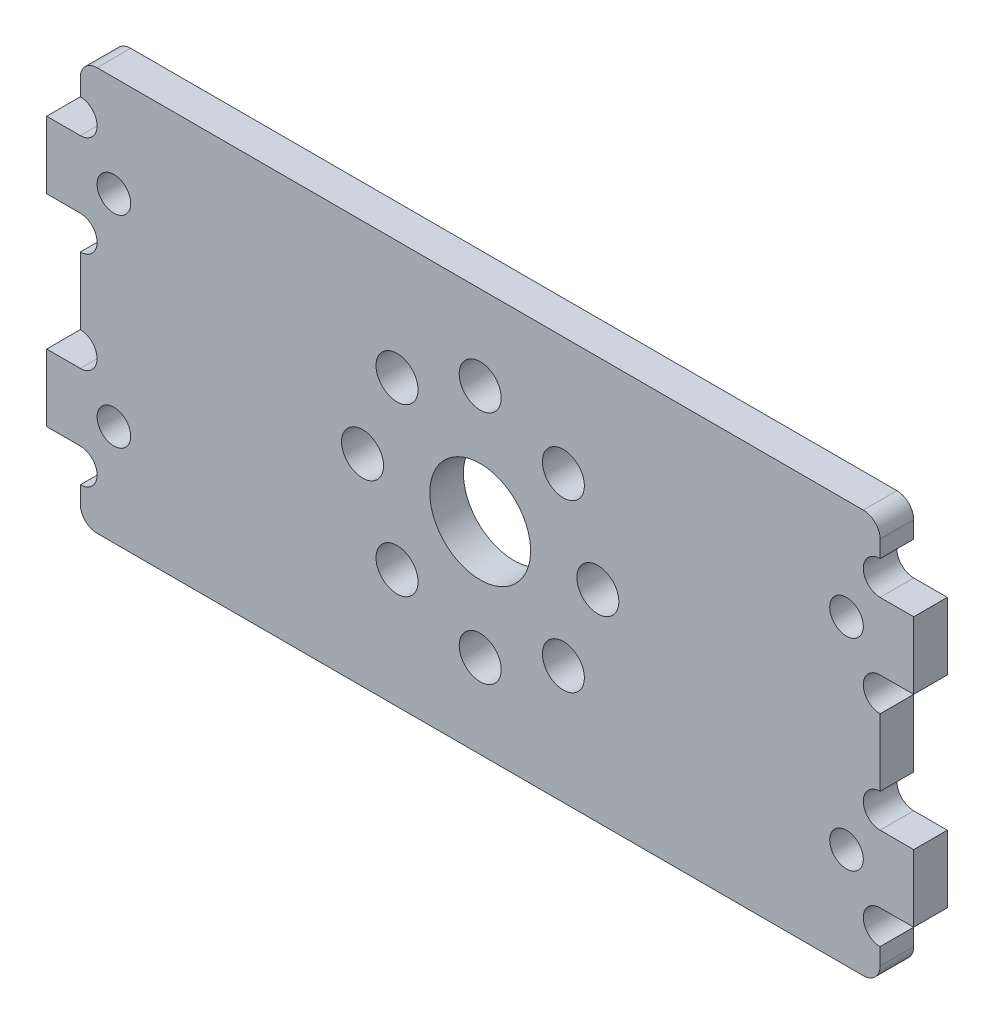
SolidWorks part; units mm, degrees
material "自訂玻璃纖維"
ref_plane "前基準面" through (0, 0, 0) normal (0, 0, 1) x (1, 0, 0)
ref_plane "上基準面" through (0, 0, 0) normal (0, 1, 0) x (1, 0, 0)
ref_plane "右基準面" through (0, 0, 0) normal (1, 0, 0) x (0, 0, -1)
sketch "草圖1" plane through (0, 0, 0) normal (0, 0, 1) x (1, 0, 0)
  line L0 (21.2594, 6.2775) -> (21.2594, 4.2775)
  line L1 (-26.3406, 6.2775) -> (21.2594, 6.2775)
  line L2 (-26.3406, 6.2775) -> (-26.3406, 4.2775)
  line L3 (-26.3406, -17.7225) -> (21.2594, -17.7225)
  line L4 (21.2594, 2.2775) -> (23.2594, 2.2775)
  line L5 (23.2594, 2.2775) -> (23.2594, -1.7225)
  line L6 (23.2594, -1.7225) -> (21.2594, -1.7225)
  line L7 (21.2594, -15.7225) -> (21.2594, -17.7225)
  line L8 (21.2594, -3.7225) -> (21.2594, -7.7225)
  line L9 (23.2594, -9.7225) -> (21.2594, -9.7225)
  line L10 (23.2594, -13.7225) -> (23.2594, -9.7225)
  line L11 (21.2594, -13.7225) -> (23.2594, -13.7225)
  line L12 (-26.3406, -3.7225) -> (-26.3406, -7.7225)
  line L13 (-26.3406, -13.7225) -> (-28.3406, -13.7225)
  line L14 (-28.3406, -13.7225) -> (-28.3406, -9.7225)
  line L15 (-28.3406, -9.7225) -> (-26.3406, -9.7225)
  line L16 (-28.3406, -1.7225) -> (-26.3406, -1.7225)
  line L17 (-28.3406, 2.2775) -> (-28.3406, -1.7225)
  line L18 (-26.3406, 2.2775) -> (-28.3406, 2.2775)
  line L19 (-26.3406, -15.7225) -> (-26.3406, -17.7225)
  circle A0 centre (-20.5406, -5.7225) radius 1
  circle A1 centre (15.4594, -5.7225) radius 1
  arc A2 (21.2594, 2.2775) -> (21.2594, 4.2775) centre (21.2594, 3.2775) cw
  arc A3 (21.2594, -1.7225) -> (21.2594, -3.7225) centre (21.2594, -2.7225) ccw
  arc A4 (21.2594, -9.7225) -> (21.2594, -7.7225) centre (21.2594, -8.7225) cw
  arc A5 (21.2594, -13.7225) -> (21.2594, -15.7225) centre (21.2594, -14.7225) ccw
  arc A6 (-26.3406, -13.7225) -> (-26.3406, -15.7225) centre (-26.3406, -14.7225) cw
  arc A7 (-26.3406, -9.7225) -> (-26.3406, -7.7225) centre (-26.3406, -8.7225) ccw
  arc A8 (-26.3406, -1.7225) -> (-26.3406, -3.7225) centre (-26.3406, -2.7225) cw
  arc A9 (-26.3406, 2.2775) -> (-26.3406, 4.2775) centre (-26.3406, 3.2775) ccw
  dimension "D6" = 4
  dimension "D3" = 2
  dimension "D4" = 4
  dimension "D1" = 47.6
  dimension "D2" = 24
extrude "填料-伸長2" add sketch "草圖1" along normal blind 2
sketch "草圖3" plane through (0, 0, 2) normal (0, 0, 1) x (1, 0, 0)
  circle A0 centre (19.2594, -5.7225) radius 1
  circle A1 centre (15.4594, -5.7225) radius 1 construction
  circle A2 centre (-24.3406, -3.7225) radius 1
  dimension "D1" = 2
  dimension "D2" = 0
extrude "除料-伸長1" cut sketch "草圖3" against normal blind 2
sketch "草圖4" plane through (0, 0, 0) normal (0, 0, -1) x (-1, 0, 0)
  circle A0 centre (-15.4594, -5.7225) radius 1
  circle A1 centre (20.5406, -5.7225) radius 1
extrude "填料-伸長4" add sketch "草圖4" against normal blind 2
sketch "草圖5" plane through (0, 0, 0) normal (0, 0, -1) x (-1, 0, 0)
  line L0 (26.3406, -17.7225) -> (-21.2594, -17.7225) construction
  circle A0 centre (2.5406, -5.7225) radius 3
  circle A1 centre (2.5406, 1.2775) radius 1.25
  circle A2 centre (7.4904, -0.7727) radius 1.25
  circle A3 centre (9.5406, -5.7225) radius 1.25
  circle A4 centre (7.4904, -10.6722) radius 1.25
  circle A5 centre (2.5406, -12.7225) radius 1.25
  circle A6 centre (-2.4091, -10.6722) radius 1.25
  circle A7 centre (-4.4594, -5.7225) radius 1.25
  circle A8 centre (-2.4091, -0.7727) radius 1.25
  point P20 (2.5406, -3.7225)
  point P24 (2.5406, -5.7225)
  dimension "D1" = 2.5
  dimension "D2" = 6
  dimension "D3" = 7
  dimension "D5" = 12
  dimension "D4" = 8
extrude "除料-伸長2" cut sketch "草圖5" against normal blind 2
sketch "草圖6" plane through (0, 0, 0) normal (0, 0, -1) x (-1, 0, 0)
  circle A0 centre (-19.2594, -5.7225) radius 1
  circle A1 centre (24.3406, -3.7225) radius 1
extrude "填料-伸長6" add sketch "草圖6" against normal blind 2
sketch "草圖7" plane through (0, 0, 0) normal (0, 0, -1) x (-1, 0, 0)
  line L0 (-21.2594, 6.2775) -> (26.3406, 6.2775) construction
  line L1 (26.3406, -17.7225) -> (-21.2594, -17.7225) construction
  line L3 (26.3406, 6.2775) -> (26.3406, 4.2775) construction
  circle A0 centre (-19.2594, 0.2775) radius 1
  circle A1 centre (-19.2594, -11.7225) radius 1
  circle A2 centre (24.3406, -11.7225) radius 1
  circle A3 centre (24.3406, 0.2775) radius 1
  dimension "D1" = 6
  dimension "D2" = 6
  dimension "D5" = 2
  dimension "D6" = 2
  dimension "D7" = 2
extrude "除料-伸長3" cut sketch "草圖7" against normal blind 2
fillet "圓角3" radius 1 1 edges at (21.2594, 6.2775, 1)
fillet "圓角4" radius 1 1 edges at (21.2594, -17.7225, 1)
fillet "圓角5" radius 1 2 edges at (-26.3406, -17.7225, 1) (-26.3406, 6.2775, 1)
